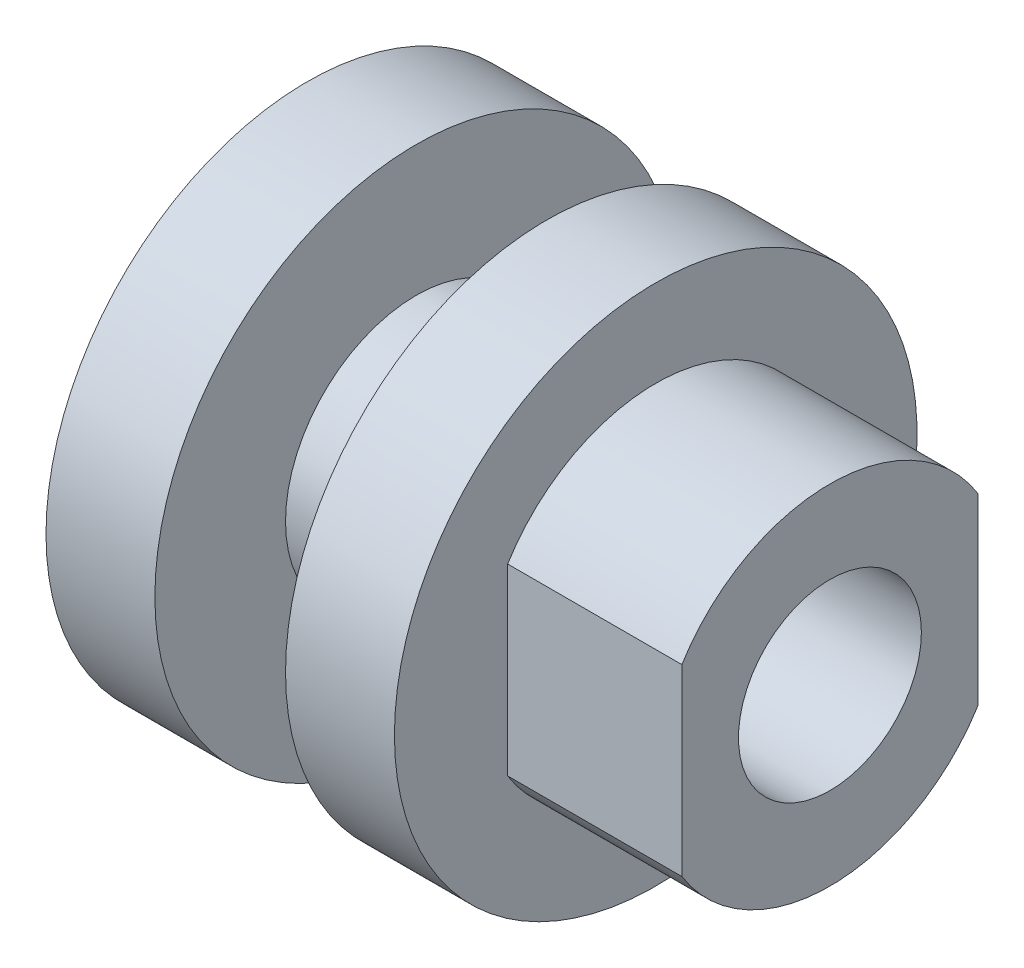
SolidWorks part; units mm, degrees
material "303"
ref_plane "前视" through (0, 0, 0) normal (0, 0, 1) x (1, 0, 0)
ref_plane "上视" through (0, 0, 0) normal (0, 1, 0) x (1, 0, 0)
ref_plane "右视" through (0, 0, 0) normal (1, 0, 0) x (0, 0, -1)
sketch "草图1" plane through (0, 0, 0) normal (0, 1, 0) x (1, 0, 0)
  line L0 (-1000, 0) -> (49000, 0) construction
  line L1 (0, 0) -> (0, 6)
  line L2 (0, 6) -> (2.5, 6)
  line L3 (2.5, 6) -> (2.5, 3)
  line L4 (2.5, 3) -> (5.5, 3)
  line L5 (5.5, 3) -> (5.5, 6)
  line L6 (5.5, 6) -> (8, 6)
  line L7 (8, 6) -> (8, 4)
  line L8 (8, 4) -> (12, 4)
  line L9 (12, 4) -> (12, 0)
  line L10 (12, 0) -> (0, 0)
  dimension "D1" = 6
  dimension "D2" = 12
  dimension "D3" = 2.5
  dimension "D4" = 3
  dimension "D5" = 12
  dimension "D6" = 8
revolve "旋转1" add sketch "草图1" angle 360 about L0
hole_wizard "M5 螺纹孔1" positions "草图5" profile "草图4" tap size "M5" standard "Gb" end condition through all
sketch "草图5" plane through (12, 0, 0) normal (1, 0, 0) x (0, 0, -1)
  point P0 (0, 0)
sketch "草图4" plane through (12, 0, 0) normal (0, 1, 0) x (0, 0, -1)
  line L0 (0, 0) -> (0, 12)
  line L1 (0, 12) -> (2.1, 12)
  line L2 (2.1, 12) -> (2.1, 0)
  line L5 (2.1, 0) -> (0, 0)
  line L11 (0, -6.35) -> (0, 107.95) construction
  dimension "通孔螺纹孔钻头直径" = 4.2
  dimension "通孔螺纹孔钻头深度" = 12
cosmetic thread "孔螺蚊线1" parameters "D2"=5
sketch "草图6" plane through (12, 0, 0) normal (1, 0, 0) x (0, 0, -1)
  line L0 (0, 0) -> (0, 5.4717) construction
  line L1 (-3.4, 2.1071) -> (-3.4, -2.1071)
  line L2 (4, 2.1071) -> (3.4, 2.1071)
  line L3 (4, 2.1071) -> (4, -2.1071)
  line L4 (4, -2.1071) -> (3.4, -2.1071)
  line L5 (3.4, 2.1071) -> (3.4, -2.1071)
  line L6 (-4, -2.1071) -> (-3.4, -2.1071)
  line L7 (-4, 2.1071) -> (-4, -2.1071)
  line L8 (-4, 2.1071) -> (-3.4, 2.1071)
  circle A0 centre (0, 0) radius 4 construction
  circle A1 centre (0, 0) radius 4 construction
  dimension "D1" = 6.8
extrude "切除-拉伸1" cut sketch "草图6" against normal up to surface (4 mm away) up to face at (8, 0, 6)
